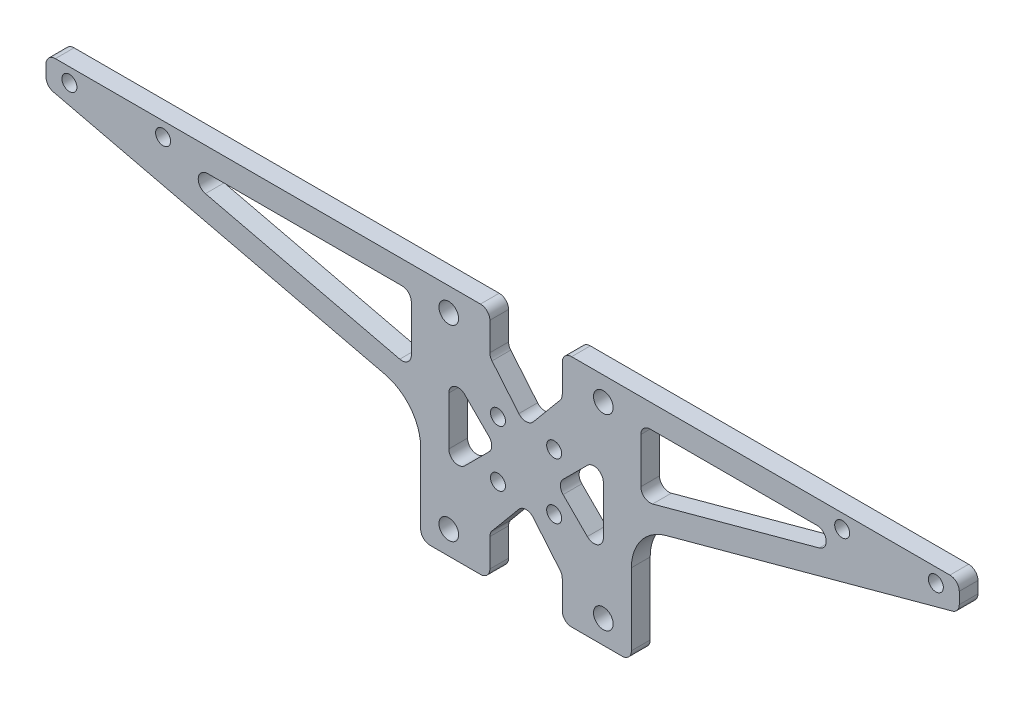
SolidWorks part; units mm, degrees
ref_plane "前视基准面" through (0, 0, 0) normal (0, 0, 1) x (1, 0, 0)
ref_plane "上视基准面" through (0, 0, 0) normal (0, 1, 0) x (1, 0, 0)
ref_plane "右视基准面" through (0, 0, 0) normal (1, 0, 0) x (0, 0, -1)
other "Configuration Table"
sketch "草图1" plane through (0, 0, 0) normal (0, 0, 1) x (1, 0, 0)
  line L0 (-102.5, 19) -> (-22.5, 0)
  line L1 (-16.5, 20) -> (16.5, 20) construction
  line L2 (-16.5, 20) -> (-16.5, -20) construction
  line L3 (-16.5, -20) -> (16.5, -20) construction
  line L4 (16.5, 20) -> (16.5, -20) construction
  line L5 (-16.5, 20) -> (16.5, -20) construction
  line L6 (-16.5, -20) -> (16.5, 20) construction
  line L7 (-22.5, 25) -> (22.5, 25)
  line L8 (-22.5, 25) -> (-22.5, -25)
  line L9 (-22.5, -25) -> (22.5, -25)
  line L10 (22.5, 25) -> (22.5, -25)
  line L11 (-22.5, 25) -> (22.5, -25) construction
  line L12 (-22.5, -25) -> (22.5, 25) construction
  line L13 (-6, 6) -> (6, 6) construction
  line L14 (-6, 6) -> (-6, -6) construction
  line L15 (-6, -6) -> (6, -6) construction
  line L16 (6, 6) -> (6, -6) construction
  line L17 (-6, 6) -> (6, -6) construction
  line L18 (-6, -6) -> (6, 6) construction
  line L19 (-102.5, 19) -> (-102.5, 25)
  line L20 (-102.5, 25) -> (-22.5, 25)
  line L21 (22.5, 25) -> (92.5, 25)
  line L22 (92.5, 25) -> (92.5, 19)
  line L23 (92.5, 19) -> (22.5, 0)
  circle A0 centre (-16.5, 20) radius 2.1
  circle A1 centre (16.5, 20) radius 2.1
  circle A2 centre (16.5, -20) radius 2.1
  circle A3 centre (-16.5, -20) radius 2.1
  circle A4 centre (-6, 6) radius 1.6
  circle A5 centre (6, 6) radius 1.6
  circle A6 centre (6, -6) radius 1.6
  circle A7 centre (-6, -6) radius 1.6
  point P0 (0, 0)
  point P10 (0, 0)
  point P15 (0, 0)
  dimension "D3" = 4.2
  dimension "D4" = 4.2
  dimension "D5" = 4.2
  dimension "D6" = 4.2
  dimension "D11" = 3.2
  dimension "D12" = 3.2
  dimension "D13" = 3.2
  dimension "D14" = 3.2
  dimension "D15" = 80
  dimension "D1" = 40
  dimension "D2" = 33
  dimension "D7" = 50
  dimension "D8" = 45
  dimension "D9" = 12
  dimension "D10" = 12
  dimension "D16" = 70
  dimension "D17" = 6
  dimension "D18" = 6
extrude "凸台-拉伸1" add sketch "草图1" along normal blind 4
fillet "圆角1" radius 2 6 edges at (92.5, 25, 2) (92.5, 19, 2) (22.5, -25, 2) (-22.5, -25, 2) (-102.5, 19, 2) (-102.5, 25, 2)
fillet "圆角2" radius 10 2 edges at (22.5, 0, 2) (-22.5, 0, 2)
sketch "草图2" plane through (0, 0, 4) normal (0, 0, 1) x (1, 0, 0)
  line L0 (0, 0) -> (0, 25) construction
  line L1 (-100.5, 25) -> (90.5, 25) construction
  line L2 (-10, 19) -> (10, 19)
  line L3 (0, 19) -> (0, 7) construction
  line L4 (0, 7) -> (-10, 19)
  line L5 (0, 7) -> (10, 19)
  line L9 (0, -7) -> (-10, -19)
  line L10 (0, -7) -> (10, -19)
  line L11 (10, -19) -> (-10, -19)
  line L15 (-19, -10) -> (-19, 10) [skipped]
  line L16 (-7, 0) -> (-8.4042, 1.1702) [skipped]
  line L17 (-7, 0) -> (-8.4042, -1.1702) [skipped]
  line L18 (8.4042, -1.1702) -> (19, -10) [skipped]
  line L19 (8.4042, 1.1702) -> (19, 10) [skipped]
  line L20 (19, 10) -> (19, -10) [skipped]
  circle A0 centre (0, 0) radius 8.4853 construction
  circle A1 centre (0, 0) radius 8.4853 construction
  circle A2 centre (0, 0) radius 8.4853 construction
  circle A3 centre (0, 0) radius 8.4853 construction
  point P25 (0, 0)
  dimension "D4" = 16.9706
  dimension "D1" = 7
  dimension "D2" = 6
  dimension "D3" = 10
  dimension "D5" = 4
extrude "切除-拉伸1" cut sketch "草图2" against normal blind 10
fillet "圆角3" radius 2 6 edges at (0, 7, 2) (0, -7, 2) (10, -19, 2) (-10, -19, 2) (10, 19, 2) (-10, 19, 2)
sketch "草图3" plane through (0, 0, 0) normal (0, 0, -1) x (-1, 0, 0)
  line L0 (0, 25) -> (0, -25) construction
  line L1 (20.5, -25) -> (-20.5, -25) construction
  line L2 (-5.7299, -19) -> (-5.7299, -25)
  line L3 (-5.7299, -25) -> (5.7299, -25)
  line L4 (0, -25) -> (0, -19)
  line L5 (5.7299, -19) -> (-5.7299, -19) construction
  line L6 (5.7299, -19) -> (-5.7299, -19)
  line L7 (-8.1241, 0) -> (8.1241, 0) construction
  line L8 (5.7299, -19) -> (5.7299, -25)
  line L9 (5.7299, 19) -> (5.7299, 25)
  line L10 (5.7299, 19) -> (-5.7299, 19)
  line L11 (0, 25) -> (0, 19)
  line L12 (-5.7299, 25) -> (5.7299, 25)
  line L13 (-5.7299, 19) -> (-5.7299, 25)
  point P19 (0, 0)
  line M5 (5.7299, -19) -> (-5.7299, -19)
  line M21 (-5.7299, 19) -> (5.7299, 19)
  line M25 (100.5, 25) -> (-90.5, 25)
  line M33 (-20.5, -25) -> (20.5, -25)
extrude "切除-拉伸2" cut sketch "草图3" against normal blind 10 contours L11 L10 L9 M25 | L13 L11 M21 M25 | L8 L4 L3 M5 | L4 L2 M33 M5
sketch "草图4" plane through (0, 0, 0) normal (0, 0, -1) x (-1, 0, 0)
  line L0 (-7.7299, 25) -> (-7.7299, 17)
  line L1 (-5.7299, 25) -> (-90.5, 25) construction
  line L2 (-7.7299, 25) -> (7.7299, 25)
  line L3 (0, 25) -> (0, 19)
  line L4 (5.7299, 19) -> (-5.7299, 19)
  line L5 (0, 25) -> (0, -25) construction
  line L6 (0, 0) -> (8.1241, 0) construction
  line L7 (7.7299, 25) -> (7.7299, 17)
  line L9 (7.7299, -25) -> (7.7299, -17)
  line L10 (5.7299, -19) -> (-5.7299, -19)
  line L11 (0, -25) -> (0, -19)
  line L12 (-7.7299, -25) -> (7.7299, -25)
  line L13 (-7.7299, -25) -> (-7.7299, -17)
  arc A0 (-5.7299, 19) -> (-7.2664, 15.7196) centre (-5.7299, 17) ccw construction
  arc A1 (-5.7299, 19) -> (-7.2664, 15.7196) centre (-5.7299, 17) ccw
  arc A3 (5.7299, 19) -> (7.2664, 15.7196) centre (5.7299, 17) cw
  arc A4 (5.7299, -19) -> (7.2664, -15.7196) centre (5.7299, -17) ccw
  arc A5 (-5.7299, -19) -> (-7.2664, -15.7196) centre (-5.7299, -17) cw
  line M29 (100.5, 25) -> (5.7299, 25)
  line M30 (5.7299, 25) -> (5.7299, 19)
  arc M31 (5.7299, 19) -> (7.2664, 15.7196) centre (5.7299, 17) cw
  arc M35 (-7.2664, 15.7196) -> (-5.7299, 19) centre (-5.7299, 17) cw
  line M36 (-5.7299, 19) -> (-5.7299, 25)
  line M37 (-5.7299, 25) -> (-90.5, 25)
  line M45 (-20.5, -25) -> (-5.7299, -25)
  line M46 (-5.7299, -25) -> (-5.7299, -19)
  arc M47 (-5.7299, -19) -> (-7.2664, -15.7196) centre (-5.7299, -17) cw
  arc M51 (7.2664, -15.7196) -> (5.7299, -19) centre (5.7299, -17) cw
  line M52 (5.7299, -19) -> (5.7299, -25)
  line M53 (5.7299, -25) -> (20.5, -25)
extrude "切除-拉伸3" cut sketch "草图4" against normal blind 10 contours A1 L4 L3 L2 L0 | L4 A3 L7 L2 L3 | A4 L10 L11 L12 L9 | L10 A5 L13 L12 L11 | L7 M29 M30 M31 | L0 M37 M35 M36 | L13 M45 M46 M47 | L9 M53 M51 M52
fillet "圆角4" radius 2 4 edges at (7.7299, -25, 2) (-7.7299, -25, 2) (-7.7299, 25, 2) (7.7299, 25, 2)
sketch "草图6" plane through (0, 0, 4) normal (0, 0, 1) x (1, 0, 0)
  line L0 (-22.895, 0) -> (22.895, 0) construction
  line L1 (6.5, 0) -> (16.5, 10)
  line L2 (16.5, 10) -> (16.5, -10)
  line L3 (6.5, 0) -> (16.5, 0) construction
  line L4 (22.5, -7.6475) -> (22.5, -23) construction
  line L5 (6.5, 0) -> (16.5, -10)
  line L6 (0, 0) -> (0, 6.2721) construction
  line L7 (-6.5, 0) -> (-16.5, 0) construction
  line L8 (-6.5, 0) -> (-16.5, -10)
  line L9 (-16.5, 10) -> (-16.5, -10)
  line L10 (-6.5, 0) -> (-16.5, 10)
  dimension "D1" = 6
  dimension "D2" = 10
  dimension "D3" = 10
extrude "切除-拉伸4" cut sketch "草图6" against normal blind 10
fillet "圆角5" radius 2 6 edges at (-16.5, -10, 2) (16.5, 10, 2) (16.5, -10, 2) (6.5, 0, 2) (-6.5, 0, 2) (-16.5, 10, 2)
sketch "草图7" plane through (0, 0, 4) normal (0, 0, 1) x (1, 0, 0)
  line L1 (-85.0723, 20) -> (-24.5, 5.6141)
  line L2 (-24.5, 5.6141) -> (-24.5, 20)
  line L3 (-24.5, 20) -> (-85.0723, 20)
  line L4 (-100.9621, 18.6348) -> (-30.1893, 1.8262) construction
  line L5 (-100.5, 25) -> (-9.7299, 25) construction
  line L7 (-16.5, 5.1716) -> (-16.5, -5.1716) construction
  line L8 (24.5, 20) -> (24.5, 5.7238)
  line L9 (24.5, 5.7238) -> (77.0966, 20)
  line L11 (77.0966, 20) -> (24.5, 20)
  line L12 (91.0239, 18.5993) -> (29.8805, 2.0033) construction
  line L13 (9.7299, 25) -> (90.5, 25) construction
  line L16 (16.5, -5.1716) -> (16.5, 5.1716) construction
  point P1 (75.3697, 20)
  point P8 (-85.2033, 20)
  point P9 (-85.0679, 20)
  point P10 (0, 0)
  point P17 (76.2057, 19.7582)
  point P25 (0, 0)
  dimension "D1" = 5
  dimension "D2" = 5
  dimension "D4" = 8
  dimension "D5" = 5
  dimension "D6" = 5
  dimension "D8" = 8
extrude "切除-拉伸5" cut sketch "草图7" against normal blind 10
sketch "草图8" plane through (0, 0, 4) normal (0, 0, 1) x (1, 0, 0)
  line L0 (-102.5, 22) -> (-80.3037, 22) construction
  line L1 (-102.5, 20.5806) -> (-102.5, 23) construction
  line L2 (-100.5, 25) -> (-9.7299, 25) construction
  circle A0 centre (-97.5, 22) radius 1.6
  circle A1 centre (-77.5, 22) radius 1.6
  dimension "D1" = 3.2
  dimension "D2" = 3.2
  dimension "D3" = 3
  dimension "D4" = 5
  dimension "D5" = 20
extrude "切除-拉伸6" cut sketch "草图8" against normal blind 10
sketch "草图9" plane through (0, 0, 4) normal (0, 0, 1) x (1, 0, 0)
  line L0 (92.5, 22) -> (67.5, 22) construction
  line L1 (92.5, 23) -> (92.5, 20.5295) construction
  line L2 (9.7299, 25) -> (90.5, 25) construction
  circle A0 centre (87.5, 22) radius 1.6
  circle A1 centre (67.5, 22) radius 1.6
  point P8 (68.333, 22.1381)
  dimension "D1" = 3.2
  dimension "D2" = 3.2
  dimension "D3" = 20
  dimension "D5" = 5
  dimension "D4" = 3
extrude "切除-拉伸7" cut sketch "草图9" against normal blind 10
fillet "圆角8" radius 2 6 edges at (24.5, 5.7238, 2) (24.5, 20, 2) (77.0966, 20, 2) (-24.5, 5.6141, 2) (-24.5, 20, 2) (-85.0723, 20, 2)
